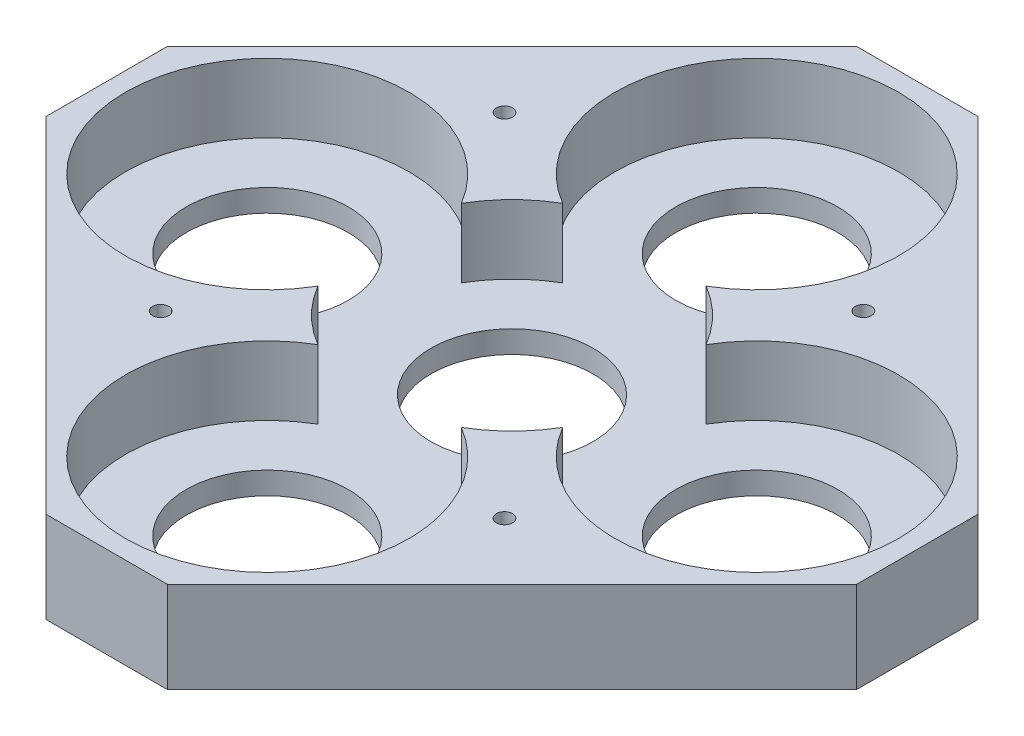
SolidWorks part; units mm, degrees
material "Pine"
ref_plane "Front Plane" through (0, 0, 0) normal (0, 0, 1) x (1, 0, 0)
ref_plane "Top Plane" through (0, 0, 0) normal (0, 1, 0) x (1, 0, 0)
ref_plane "Right Plane" through (0, 0, 0) normal (1, 0, 0) x (0, 0, -1)
ref_plane "Plane1" through (0, 28.575, 0) normal (0, 1, 0) x (1, 0, 0)
sketch "Sketch1" plane through (0, 28.575, 0) normal (0, 1, 0) x (1, 0, 0)
  line L0 (127, 273.05) -> (-19.05, 127)
  line L1 (-19.05, 127) -> (127, -19.05)
  line L2 (127, -19.05) -> (273.05, 127)
  line L3 (273.05, 127) -> (127, 273.05)
extrude "Boss-Extrude1" add sketch "Sketch1" against normal blind 28.575
sketch "Sketch2" plane through (0, 28.575, 0) normal (0, 1, 0) x (-1, 0, 0)
  arc A0 (-149.4672, -88.646) -> (-165.354, -104.5328) centre (-127, -127) ccw
  arc A1 (-165.354, -104.5328) -> (-165.354, -149.4672) centre (-203.708, -127) ccw
  arc A2 (-165.354, -149.4672) -> (-149.4672, -165.354) centre (-127, -127) ccw
  arc A3 (-149.4672, -165.354) -> (-104.5328, -165.354) centre (-127, -203.708) ccw
  arc A4 (-104.5328, -165.354) -> (-88.646, -149.4672) centre (-127, -127) ccw
  arc A5 (-88.646, -149.4672) -> (-88.646, -104.5328) centre (-50.292, -127) ccw
  arc A6 (-88.646, -104.5328) -> (-104.5328, -88.646) centre (-127, -127) ccw
  arc A7 (-104.5328, -88.646) -> (-149.4672, -88.646) centre (-127, -50.292) ccw
extrude "Cut-Extrude1" cut sketch "Sketch2" against normal blind 21.59
hole_wizard "#8 (0.199) Diameter Hole1" positions "Sketch4" profile "Sketch3" hole size "#8" standard "ANSI Inch"
sketch "Sketch4" plane through (0, 28.575, 0) normal (0, 1, 0) x (1, 0, 0)
  point P0 (180.8815, 183.2474)
  point P1 (180.8815, 70.7526)
  point P2 (70.7526, 73.1185)
  point P3 (70.7526, 180.8815)
sketch "Sketch3" plane through (180.8815, 28.575, -183.2474) normal (1, 0, 0) x (0, 0, 1)
  line L0 (0, 0) -> (0, 28.575)
  line L1 (0, 28.575) -> (2.5273, 28.575)
  line L2 (2.5273, 28.575) -> (2.5273, 0)
  line L5 (2.5273, 0) -> (0, 0)
  line L11 (0, -6.35) -> (0, 107.95) construction
  dimension "Thru Hole Dia." = 5.0546
  dimension "Thru Hole Depth" = 28.575
hole_wizard "Hole1" positions "Sketch6" profile "Sketch5" legacy
sketch "Sketch6" plane through (0, 6.985, 0) normal (0, 1, 0) x (1, 0, 0)
  point P0 (127, 127)
  point P1 (127, 203.708)
  point P2 (50.292, 127)
  point P3 (127, 50.292)
  point P4 (203.708, 127)
sketch "Sketch5" plane through (127, 6.985, -127) normal (1, 0, 0) x (0, 0, 1)
  line L0 (0, 0) -> (0, 6.985)
  line L1 (0, 6.985) -> (25.4, 6.985)
  line L2 (25.4, 6.985) -> (25.4, 0)
  line L3 (25.4, 0) -> (0, 0)
  line L4 (0, 110) -> (0, -10) construction
  dimension "Diameter" = 50.8
  dimension "Depth" = 6.985
chamfer "Chamfer1" distance 26.9408 angle 45 4 edges at (127, 14.2875, -273.05) (273.05, 14.2875, -127) (-19.05, 14.2875, -127) (127, 14.2875, 19.05)
